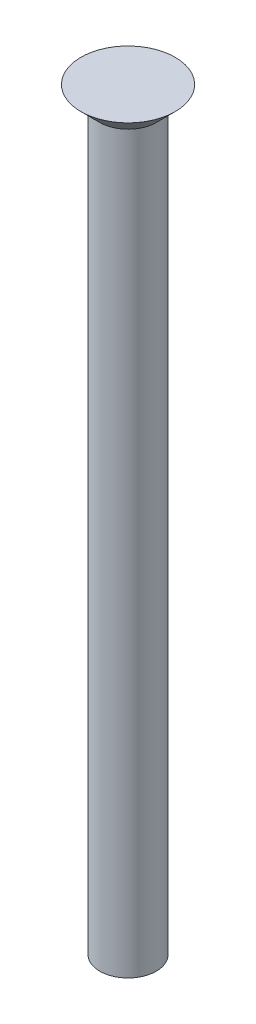
SolidWorks part; units mm, degrees
ref_plane "Front Plane" through (0, 0, 0) normal (0, 0, 1) x (1, 0, 0)
ref_plane "Top Plane" through (0, 0, 0) normal (0, 1, 0) x (1, 0, 0)
ref_plane "Right Plane" through (0, 0, 0) normal (1, 0, 0) x (0, 0, -1)
sketch "vf" plane through (0, 0, 0) normal (0, 0, 1) x (1, 0, 0)
  line L0 (0, 0) -> (0, 40) construction
  line L1 (0, 40) -> (-2.5, 40)
  line L2 (-2.5, 40) -> (-1.5, 39)
  line L3 (-1.5, 39) -> (-1.5, 0)
  line L4 (-1.5, 0) -> (0, 0)
  line L5 (0, 0) -> (0, 40)
  dimension "D1" = 40
  dimension "D2" = 1.5
  dimension "D3" = 2.5
  dimension "D4" = 45
revolve "Revolve1" add sketch "vf" angle 360 about L0
